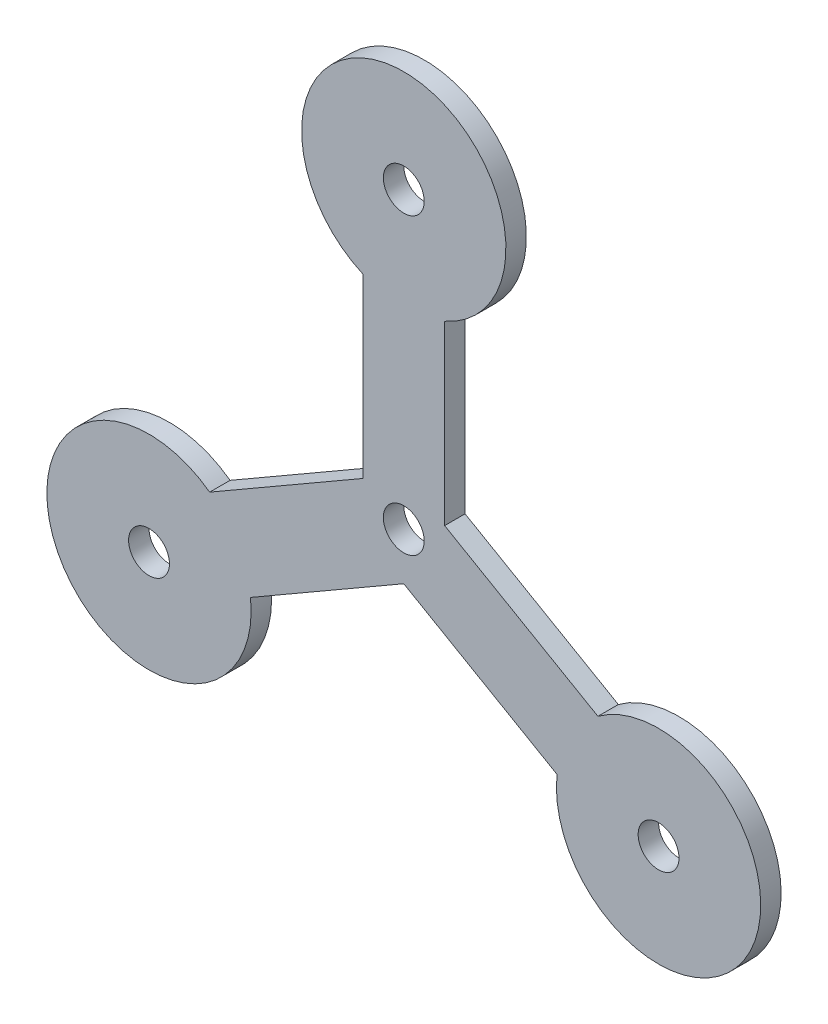
SolidWorks part; units mm, degrees
ref_plane "Front Plane" through (0, 0, 0) normal (0, 0, 1) x (1, 0, 0)
ref_plane "Top Plane" through (0, 0, 0) normal (0, 1, 0) x (1, 0, 0)
ref_plane "Right Plane" through (0, 0, 0) normal (1, 0, 0) x (0, 0, -1)
sketch "Sketch1" plane through (0, 0, 0) normal (0, 0, 1) x (1, 0, 0)
  line L0 (0, 0) -> (0, 144) construction
  line L1 (20, 144) -> (-20, 144)
  line L6 (0, 0) -> (124.7077, -72) construction
  line L7 (0, 0) -> (-124.7077, -72) construction
  line L8 (114.7077, -89.3205) -> (134.7077, -54.6795)
  line L9 (-114.7077, -89.3205) -> (-134.7077, -54.6795)
  line L10 (-134.7077, -54.6795) -> (-20, 11.547)
  line L11 (-20, 11.547) -> (-20, 144)
  line L12 (20, 144) -> (20, 11.547)
  line L13 (20, 11.547) -> (134.7077, -54.6795)
  line L14 (114.7077, -89.3205) -> (0, -23.094)
  line L15 (0, -23.094) -> (-114.7077, -89.3205)
  point P6 (0, 144)
  point P10 (0, 0)
  point P12 (124.7077, -72)
  point P15 (-124.7077, -72)
  dimension "D1" = 3
extrude "Boss-Extrude2" add sketch "Sketch1" along normal blind 10
sketch "Sketch3" plane through (0, 0, 10) normal (0, 0, 1) x (1, 0, 0)
  line L0 (-134.7077, -54.6795) -> (-114.7077, -89.3205) construction
  circle A0 centre (-124.7077, -72) radius 50
  circle A1 centre (0, 144) radius 50
  circle A2 centre (124.7077, -72) radius 50
  point P11 (0, 0)
  dimension "D1" = 3
extrude "Boss-Extrude3" add sketch "Sketch3" against normal blind 10
sketch "Sketch4" plane through (0, 0, 10) normal (0, 0, 1) x (1, 0, 0)
  circle A1 centre (0, 144) radius 10
  circle A2 centre (124.7077, -72) radius 10
  circle A3 centre (-124.7077, -72) radius 10
  point P9 (0, 0)
  dimension "D1" = 3
extrude "Boss-Extrude4" add sketch "Sketch4" along normal blind 90
sketch "Sketch5" plane through (0, 0, 100) normal (0, 0, 1) x (1, 0, 0)
  circle A0 centre (0, 144) radius 10
extrude "Cut-Extrude1" cut sketch "Sketch5" against normal blind 30
sketch "Sketch6" plane through (0, 0, 10) normal (0, 0, 1) x (1, 0, 0)
  circle A0 centre (0, 0) radius 13
extrude "Cut-Extrude2" cut sketch "Sketch6" against normal blind 10
sketch "Sketch7" plane through (0, 0, 70) normal (0, 0, 1) x (1, 0, 0)
  circle A0 centre (0, 144) radius 10
extrude "Boss-Extrude5" add sketch "Sketch7" along normal blind 30
sketch "Sketch8" plane through (0, 0, 10) normal (0, 0, 1) x (1, 0, 0)
  circle A0 centre (0, 0) radius 20.3692
extrude "Boss-Extrude6" add sketch "Sketch8" against normal blind 10
sketch "Sketch9" plane through (0, 0, 100) normal (0, 0, 1) x (1, 0, 0)
  circle A0 centre (-124.7077, -72) radius 10
  circle A1 centre (0, 144) radius 10
  circle A2 centre (124.7077, -72) radius 10
  point P10 (0, 0)
  dimension "D1" = 3
extrude "Cut-Extrude3" cut sketch "Sketch9" against normal blind 100
sketch "Sketch10" plane through (0, 0, 10) normal (0, 0, 1) x (1, 0, 0)
  circle A0 centre (0, 0) radius 10
extrude "Cut-Extrude4" cut sketch "Sketch10" against normal blind 10
